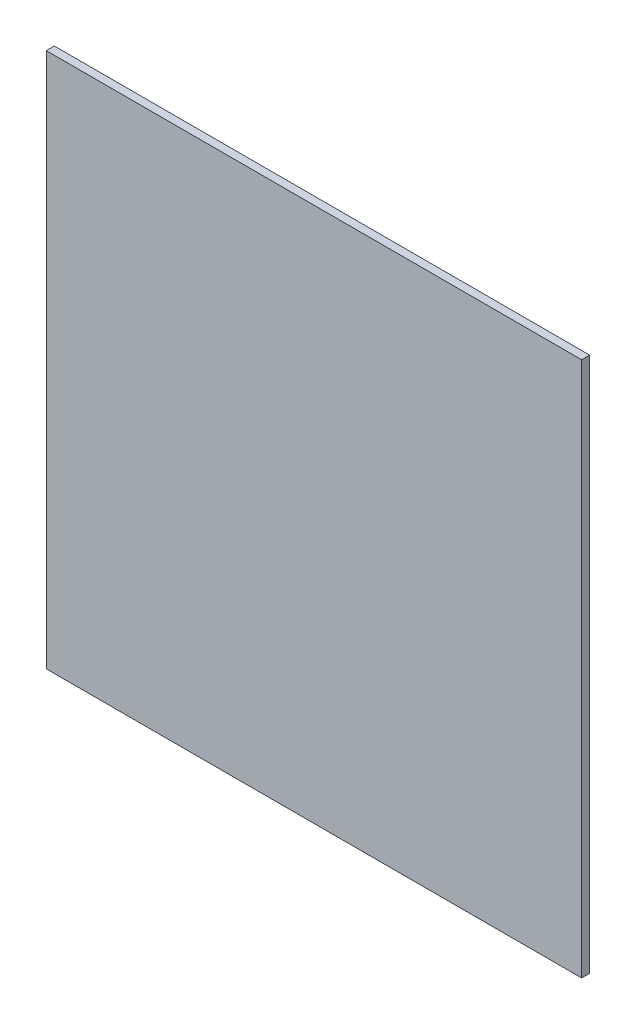
SolidWorks part; units mm, degrees
material "Vidro"
ref_plane "Plano frontal" through (0, 0, 0) normal (0, 0, 1) x (1, 0, 0)
ref_plane "Plano superior" through (0, 0, 0) normal (0, 1, 0) x (1, 0, 0)
ref_plane "Plano direito" through (0, 0, 0) normal (1, 0, 0) x (0, 0, -1)
sketch "Esboço1" plane through (0, 0, 0) normal (0, 0, 1) x (1, 0, 0)
  line L1 (-100, 100) -> (100, 100)
  line L2 (-100, 100) -> (-100, -100)
  line L3 (-100, -100) -> (100, -100)
  line L4 (100, 100) -> (100, -100)
  line L5 (-100, 100) -> (100, -100) construction
  line L6 (-100, -100) -> (100, 100) construction
  point P0 (0, 0)
  dimension "D1" = 200
extrude "Ressalto-extrusão1" add sketch "Esboço1" along normal blind 3
